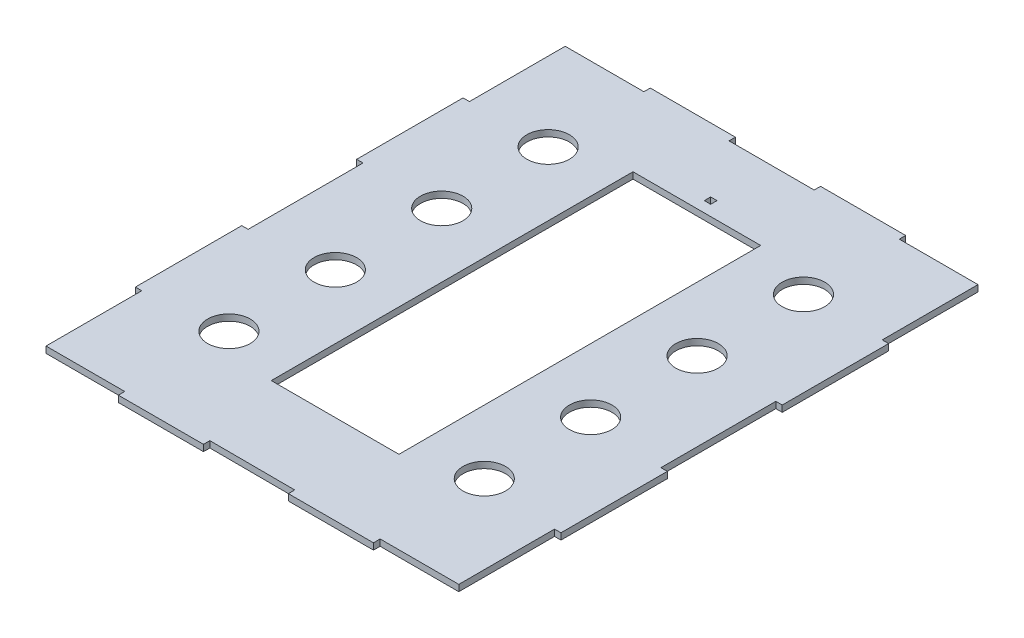
SolidWorks part; units mm, degrees
material "Acrylic (Medium-high impact)"
ref_plane "Alzado" through (0, 0, 0) normal (0, 0, 1) x (1, 0, 0)
ref_plane "Planta" through (0, 0, 0) normal (0, 1, 0) x (1, 0, 0)
ref_plane "Vista lateral" through (0, 0, 0) normal (1, 0, 0) x (0, 0, -1)
sketch "Sketch1" plane through (0, 0, 0) normal (0, 1, 0) x (1, 0, 0)
  line L0 (20, 123.1327) -> (60, 123.1327)
  line L1 (-60, 123.1327) -> (-20, 123.1327)
  line L3 (-60, -126.8673) -> (-20, -126.8673)
  line L4 (100, 75.1327) -> (100, 25.1327)
  line L5 (0, 0) -> (0, 120.1327) construction
  line L6 (-100, -28.8673) -> (-100, -78.8673)
  line L7 (-97, 120.1327) -> (-60, 120.1327)
  line L8 (-60, 120.1327) -> (-60, 123.1327)
  line L9 (20.0285, -127) -> (60.0285, -127)
  line L10 (-20, 123.1327) -> (-20, 120.1327)
  line L11 (-20, 120.1327) -> (20, 120.1327)
  line L12 (20, 120.1327) -> (20, 123.1327)
  line L13 (60.0285, -127) -> (60.0285, -123.8673)
  line L14 (60, 123.1327) -> (60, 120.1327)
  line L15 (60, 120.1327) -> (97, 120.1327)
  line L16 (-97, 75.1327) -> (-97, 120.1327)
  line L20 (20.0285, -124) -> (20.0285, -127)
  line L21 (-19.9715, -123.8674) -> (20.0285, -124)
  line L22 (-20, -126.8673) -> (-19.9715, -123.8674)
  line L23 (60.0285, -123.8673) -> (97, -123.8673)
  line L24 (-60.028, -123.8674) -> (-60, -126.8673)
  line L25 (-97, -123.8673) -> (-60.028, -123.8674)
  line L26 (100, -124) -> (100, 120) construction
  line L27 (-100, -127) -> (100.0285, -127) construction
  line L28 (-100, -127) -> (-100, 120) construction
  line L29 (-100, 75.1327) -> (-97, 75.1327)
  line L30 (97, -123.8673) -> (97, -78.8673)
  line L31 (97, -78.8673) -> (100, -78.8673)
  line L32 (100, -78.8673) -> (100, -28.8673)
  line L33 (100, -28.8673) -> (97, -28.8673)
  line L34 (97, -28.8673) -> (97, 25.1327)
  line L35 (97, 25.1327) -> (100, 25.1327)
  line L37 (100, 75.1327) -> (97, 75.1327)
  line L38 (97, 75.1327) -> (97, 120.1327)
  line L40 (-100, 25.1327) -> (-100, 75.1327)
  line L41 (-97, 25.1327) -> (-100, 25.1327)
  line L42 (-97, -28.8673) -> (-97, 25.1327)
  line L43 (-100, -28.8673) -> (-97, -28.8673)
  line L45 (-97, -78.8673) -> (-100, -78.8673)
  line L46 (-97, -123.8673) -> (-97, -78.8673)
  point P16 (-40, -126.8673)
  dimension "D1" = 3
  dimension "D2" = 45
  dimension "D3" = 3
  dimension "D4" = 3
  dimension "D5" = 40
  dimension "D6" = 40
  dimension "D7" = 3
  dimension "D8" = 40
  dimension "D9" = 3
  dimension "D10" = 3
  dimension "D11" = 50
  dimension "D12" = 54
  dimension "D13" = 45
  dimension "D14" = 250
  dimension "D15" = 50
  dimension "D16" = 40
  dimension "D20" = 3
  dimension "D21" = 3
extrude "Boss-Extrude1" add sketch "Sketch1" along normal blind 3
sketch "Sketch2" plane through (0, 3, 0) normal (0, 1, 0) x (1, 0, 0)
  line L0 (-97, 75.1327) -> (97, 75.1327) construction
  line L1 (-97, 25.1327) -> (97, 25.1327) construction
  line L2 (-97, -28.8673) -> (97, -28.8673) construction
  line L3 (-97, -78.8673) -> (97, -78.8673) construction
  line L4 (-97, -78.8673) -> (-97, -123.8673) construction
  line L5 (-60.028, 120.1326) -> (-60.028, -123.8674) construction
  line L6 (-20, 120.1327) -> (-20, -123.8674) construction
  line L7 (20, 120.1327) -> (20, -124) construction
  line L8 (60, 120.1327) -> (60, -123.8673) construction
  line L9 (-30, 85) -> (-30, -85)
  line L20 (-112.676, 0) -> (110.1306, 0) construction
  line L28 (-30, -85) -> (30, -85)
  line L29 (30, -85) -> (30, 85)
  line L35 (-30, 85) -> (30, 85)
  line L36 (0, 85) -> (0, 90) construction
  line L37 (0, 90) -> (-1.5, 90)
  line L38 (-1.5, 90) -> (-1.5, 93)
  line L39 (-1.5, 93) -> (1.5, 93)
  line L40 (1.5, 93) -> (1.5, 90)
  line L41 (1.5, 90) -> (0, 90)
  circle A0 centre (-60.028, 75.1327) radius 10
  circle A3 centre (59.972, 75.1327) radius 10
  circle A4 centre (-60.028, 25.1327) radius 10
  circle A7 centre (59.972, 25.1327) radius 10
  circle A8 centre (-60.028, -24.8673) radius 10
  circle A11 centre (59.972, -24.8673) radius 10
  circle A12 centre (-60.028, -74.8673) radius 10
  circle A15 centre (59.972, -74.8673) radius 10
  circle A23 centre (-20.028, 75.1327) radius 10 [skipped]
  circle A24 centre (19.972, 75.1327) radius 10 [skipped]
  point P76 (0, -15)
  dimension "D1" = 4
  dimension "D3" = 3
  dimension "D4" = 3
  dimension "D5" = 1.5
  dimension "D2" = 4
extrude "Cut-Extrude1" cut sketch "Sketch2" against normal through all
